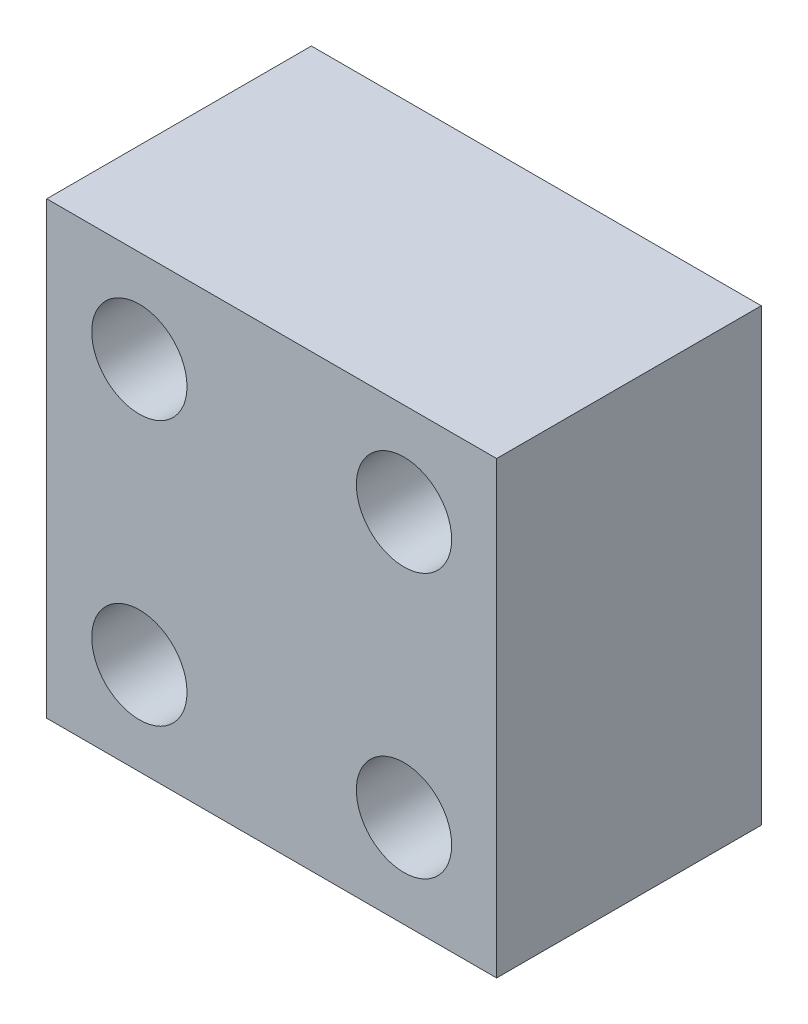
SolidWorks part; units mm, degrees
ref_plane "Front Plane" through (0, 0, 0) normal (0, 0, 1) x (1, 0, 0)
ref_plane "Top Plane" through (0, 0, 0) normal (0, 1, 0) x (1, 0, 0)
ref_plane "Right Plane" through (0, 0, 0) normal (1, 0, 0) x (0, 0, -1)
sketch "Sketch1" plane through (0, 0, 0) normal (0, 0, 1) x (1, 0, 0)
  line L0 (169, 103.999) -> (152, 103.999)
  line L1 (152, 86.999) -> (152, 112.099) construction
  line L2 (152, 86.999) -> (169, 86.999) construction
  line L3 (169, 86.999) -> (169, 112.099) construction
  line L8 (169, 86.999) -> (169, 103.999)
  line L10 (152, 103.999) -> (152, 86.999)
  line L11 (152, 86.999) -> (169, 86.999)
  dimension "D2" = 17
extrude "Boss-Extrude1" add sketch "Sketch1" along normal blind 10
sketch "Sketch2" plane through (0, 0, 10) normal (0, 0, 1) x (1, 0, 0)
  point P12 (155.5, 100.499)
  point P15 (155.5, 90.499)
  point P18 (165.5, 90.499)
  point P21 (165.5, 100.499)
hole_wizard "M3 Clearance Hole1" positions "Sketch2" profile "Sketch3" hole size "M3" standard "ANSI Metric" end condition through all
sketch "Sketch3" plane through (155.5, 100.499, 10) normal (1, 0, 0) x (0, -1, 0)
  line L0 (0, 0) -> (0, 10)
  line L1 (0, 10) -> (1.8, 10)
  line L2 (1.8, 10) -> (1.8, 0)
  line L5 (1.8, 0) -> (0, 0)
  line L11 (0, -6.35) -> (0, 107.95) construction
  dimension "Thru Hole Dia." = 3.6
  dimension "Thru Hole Depth" = 10
